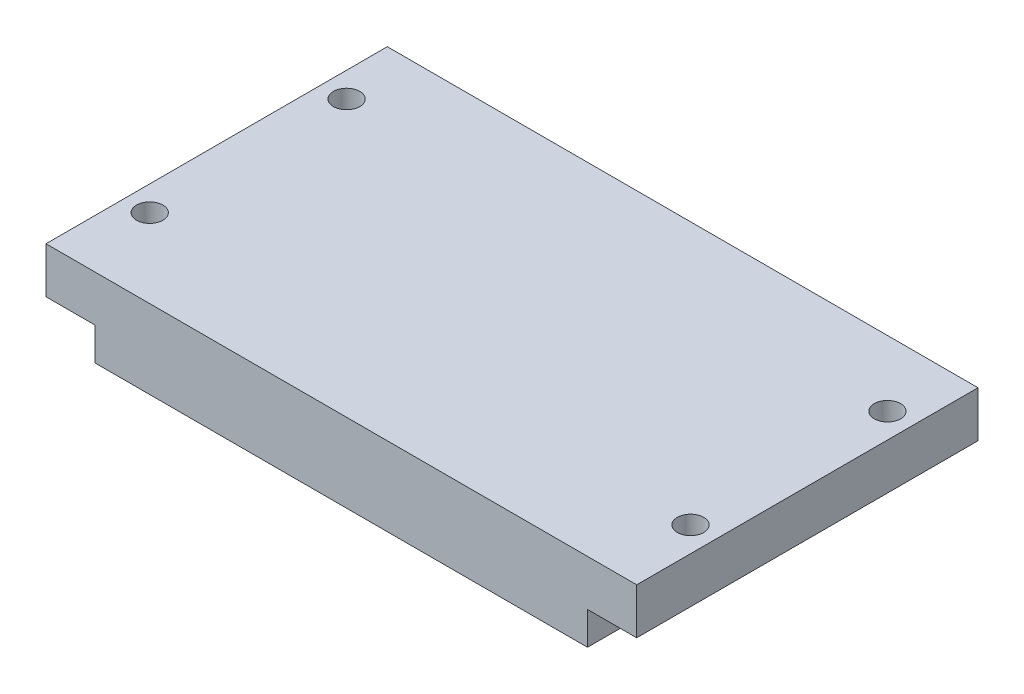
SolidWorks part; units mm, degrees
material "ABS"
ref_plane "Front Plane" through (0, 0, 0) normal (0, 0, 1) x (1, 0, 0)
ref_plane "Top Plane" through (0, 0, 0) normal (0, 1, 0) x (1, 0, 0)
ref_plane "Right Plane" through (0, 0, 0) normal (1, 0, 0) x (0, 0, -1)
sketch "Sketch2" plane through (0, 0, 0) normal (0, 0, 1) x (1, 0, 0)
  line L0 (0, 0) -> (114.3, 0)
  line L1 (0, 0) -> (0, -8.89)
  line L2 (0, -8.89) -> (9.525, -8.89)
  line L3 (9.525, -8.89) -> (9.525, -15.24)
  line L4 (114.3, 0) -> (114.3, -8.89)
  line L5 (114.3, -8.89) -> (104.775, -8.89)
  line L6 (104.775, -8.89) -> (104.775, -15.24)
  line L7 (9.525, -15.24) -> (104.775, -15.24)
  dimension "D1" = 95.25
  dimension "D2" = 8.89
  dimension "D3" = 6.35
  dimension "D4" = 9.525
extrude "Boss-Extrude1" add sketch "Sketch2" along normal blind 66.04
hole_wizard "#10 Clearance Hole1" positions "3DSketch1" profile "Sketch3" hole size "#10" standard "Ansi Inch" end condition through all
sketch3d "3DSketch1"
  line L0 (0, 0, 12.7) -> (114.3, 0, 12.7) construction
  line L1 (0, 0, 66.04) -> (0, 0, 0) construction
  line L2 (114.3, 0, 66.04) -> (114.3, 0, 0) construction
  line L3 (114.3, 0, 0) -> (0, 0, 0) construction
  line L4 (0, 0, 50.8) -> (114.3, 0, 50.8) construction
  line L5 (4.826, 0, 0) -> (4.826, 0, 66.04) construction
  line L6 (114.3, 0, 66.04) -> (0, 0, 66.04) construction
  line L7 (109.474, 0, 0) -> (109.474, 0, 66.04) construction
  point P0 (4.826, 0, 12.7)
  point P2 (4.826, 0, 50.8)
  point P4 (109.474, 0, 50.8)
  point P6 (109.474, 0, 12.7)
  dimension "D1" = 12.7
  dimension "D2" = 38.1
  dimension "D3" = 4.826
  dimension "D4" = 4.826
sketch "Sketch3" plane through (4.826, 0, 12.7) normal (1, 0, 0) x (0, 0, 1)
  line L0 (0, 0) -> (0, 15.24)
  line L1 (0, 15.24) -> (2.5527, 15.24)
  line L2 (2.5527, 15.24) -> (2.5527, 0)
  line L5 (2.5527, 0) -> (0, 0)
  line L11 (0, -6.35) -> (0, 107.95) construction
  dimension "Thru Hole Dia." = 5.1054
  dimension "Thru Hole Depth" = 15.24
